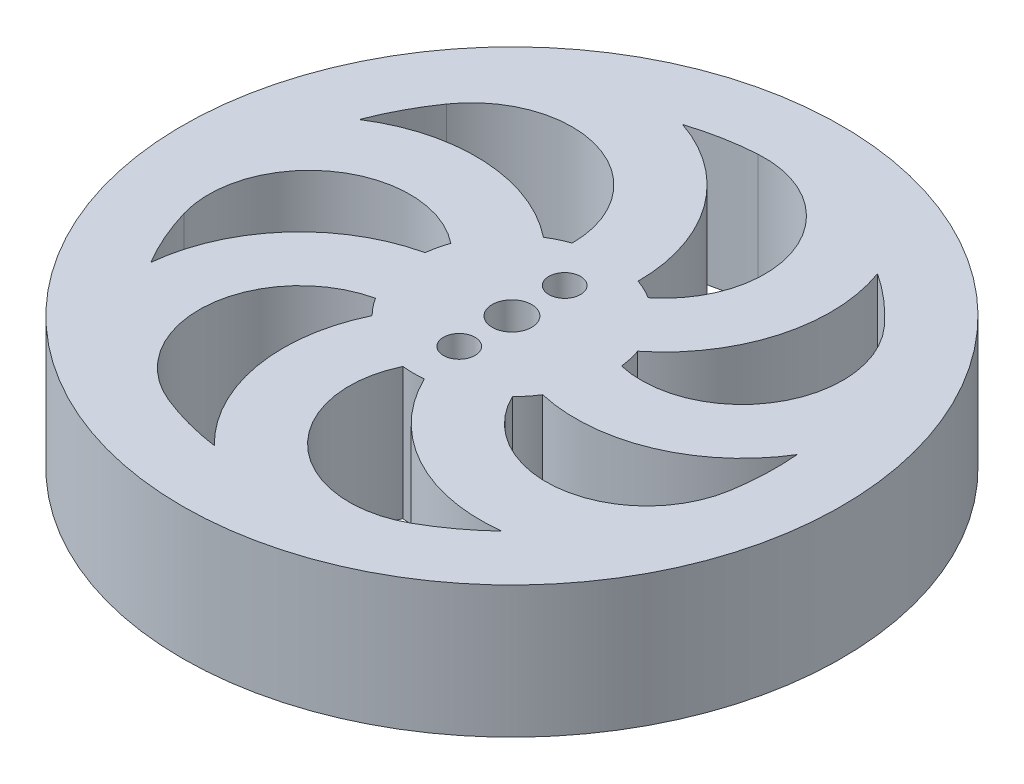
SolidWorks part; units mm, degrees
material "Rubber"
ref_plane "Front Plane" through (0, 0, 0) normal (0, 0, 1) x (1, 0, 0)
ref_plane "Top Plane" through (0, 0, 0) normal (0, 1, 0) x (1, 0, 0)
ref_plane "Right Plane" through (0, 0, 0) normal (1, 0, 0) x (0, 0, -1)
sketch "Base Reference Sketch" plane through (0, 0, 0) normal (0, 1, 0) x (1, 0, 0)
  line L0 (-2.5, 7.0711) -> (2.5, 7.0711) construction
  line L1 (0, 6.5) -> (0, 1.5) construction
  circle A0 centre (0, 0) radius 25
  circle A1 centre (0, 0) radius 20
  circle A2 centre (0, 0) radius 1.5
  circle A3 centre (0, 0) radius 7.5
  arc A4 (-2.5, 7.0711) -> (-16.4045, 11.4408) centre (-10.1389, 7.0711) ccw
  arc A5 (2.5, 7.0711) -> (-6.0997, 19.0471) centre (-10.1389, 7.0711) ccw
  arc A6 (2.5, 7.0711) -> (-20.5056, 14.301) centre (-10.1389, 7.0711) ccw construction
  circle A7 centre (0, 0) radius 6.5 construction
  point P14 (0, 4)
  point P15 (0, 3.5)
  dimension "D1" = 50
  dimension "D3" = 6
  dimension "D2" = 5
  dimension "D4" = 3
  dimension "D5" = 5
  dimension "D6" = 1
extrude "Base Wheel Extrude" add sketch "Base Reference Sketch" along normal blind 10 contours A0 A1 | A3 A5 A1 A4 | A3 A2
pattern_circular "Spokes Circular Pattern" count 7 over 360 about axis through (0, 0, 0) along (0, 1, 0) of "Base Wheel Extrude"
hole_wizard "M2 Clearance Hole1" positions "Sketch1" profile "Sketch2" hole size "M2" standard "ISO" end condition through all
sketch "Sketch1" plane through (0, 0, 0) normal (0, -1, 0) x (-1, 0, 0)
  point P0 (0, 4)
sketch "Sketch2" plane through (0, 0, -4) normal (1, 0, 0) x (0, 0, -1)
  line L0 (0, 0) -> (0, 10)
  line L1 (0, 10) -> (1.2, 10)
  line L2 (1.2, 10) -> (1.2, 0)
  line L5 (1.2, 0) -> (0, 0)
  line L11 (0, -6.35) -> (0, 107.95) construction
  dimension "Thru Hole Dia." = 2.4
  dimension "Thru Hole Depth" = 10
pattern_circular "CirPattern1" count 2 over 360 about axis through (0, 0, 0) along (0, 1, 0) of "M2 Clearance Hole1"
equation "\"wheeldia\"= 50mm"
equation "\"wheelthick\"= 3mm"
equation "\"wheelwide\"= 10mm"
equation "\"wheelspokes\"= 7"
